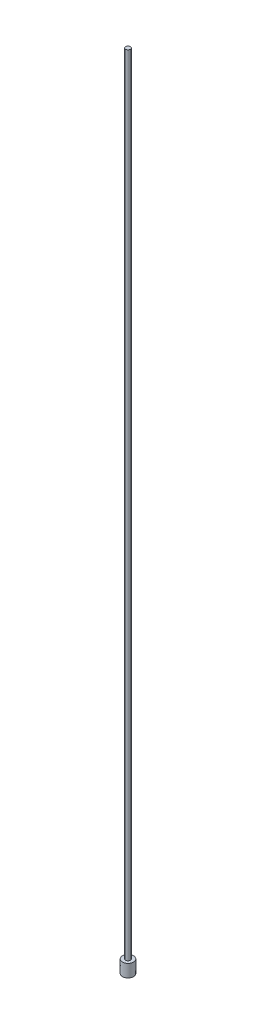
SolidWorks part; units mm, degrees
ref_plane "Front Plane" through (0, 0, 0) normal (0, 0, 1) x (1, 0, 0)
ref_plane "Top Plane" through (0, 0, 0) normal (0, 1, 0) x (1, 0, 0)
ref_plane "Right Plane" through (0, 0, 0) normal (1, 0, 0) x (0, 0, -1)
sketch "Sketch1" plane through (0, 0, 0) normal (0, 1, 0) x (1, 0, 0)
  circle A0 centre (0, 0) radius 3.5
  dimension "D1" = 7
extrude "Boss-Extrude1" add sketch "Sketch1" along normal blind 8
sketch "Sketch2" plane through (0, 8, 0) normal (0, 1, 0) x (1, 0, 0)
  circle A0 centre (0, 0) radius 1.5
  dimension "D1" = 3
extrude "Boss-Extrude2" add sketch "Sketch2" along normal blind 500
